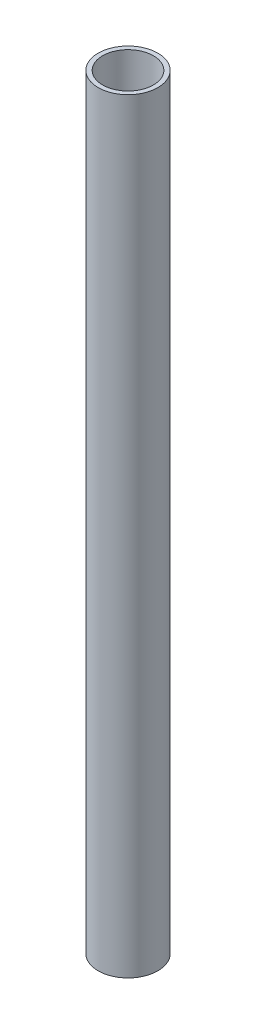
SolidWorks part; units mm, degrees
ref_plane "前视基准面" through (0, 0, 0) normal (0, 0, 1) x (1, 0, 0)
ref_plane "上视基准面" through (0, 0, 0) normal (0, 1, 0) x (1, 0, 0)
ref_plane "右视基准面" through (0, 0, 0) normal (1, 0, 0) x (0, 0, -1)
other "Configuration Table"
sketch "草图1" plane through (0, 0, 0) normal (0, 1, 0) x (1, 0, 0)
  circle A14 centre (0, 0) radius 16
  circle A15 centre (0, 0) radius 13.6
  dimension "D1" = 32
  dimension "D2" = 2.4
extrude "凸台-拉伸1" add sketch "草图1" along normal blind 410
